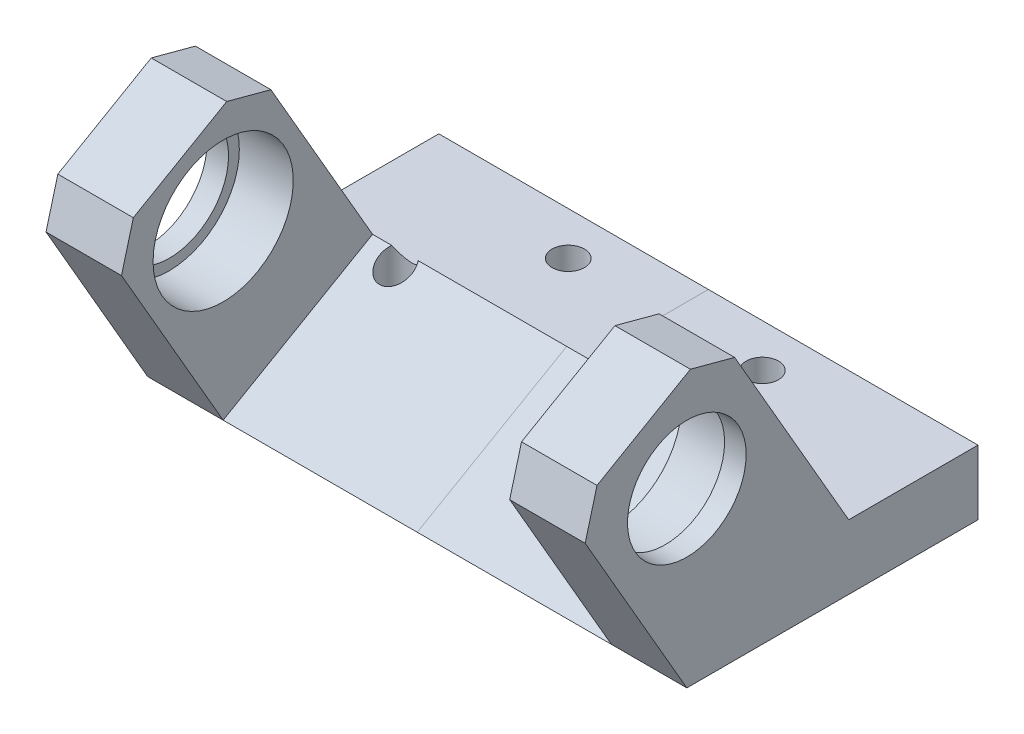
SolidWorks part; units mm, degrees
material "1060 合金"
ref_plane "前视基准面" through (0, 0, 0) normal (0, 0, 1) x (1, 0, 0)
ref_plane "上视基准面" through (0, 0, 0) normal (0, 1, 0) x (1, 0, 0)
ref_plane "右视基准面" through (0, 0, 0) normal (1, 0, 0) x (0, 0, -1)
sketch "草图1" plane through (0, 0, 0) normal (1, 0, 0) x (0, 0, -1)
  line L0 (0, 0) -> (-10.9282, 18.9282)
  line L1 (-10.9282, 18.9282) -> (2.9282, 26.9282)
  line L2 (2.9282, 26.9282) -> (15.0111, 6)
  line L3 (15.0111, 6) -> (27, 6)
  line L5 (27, 0) -> (0, 0)
  line L6 (27, 6) -> (27, 0)
  circle A0 centre (0, 16) radius 6.5
  dimension "D3" = 8
  dimension "D7" = 13
  dimension "D1" = 8
  dimension "D2" = 16
  dimension "D4" = 8
  dimension "D5" = 6
  dimension "D6" = 27
  dimension "D8" = 120
extrude "凸台-拉伸1" add sketch "草图1" along normal mid plane 50
chamfer "倒角1" distance 3 angle 45 2 edges at (0, 18.9282, 10.9282) (0, 26.9282, -2.9282)
sketch "草图2" plane through (0, 18.9282, 10.9282) normal (0, 0.866, 0.5) x (1, 0, 0)
  line L0 (0, 0) -> (0, 26.0074) construction
  line L1 (25, 0) -> (-25, 0) construction
  line L2 (25, 16) -> (-25, 16) construction
  line L3 (-18, 16) -> (18, 16)
  line L4 (-18, 16) -> (-18, 0)
  line L5 (-18, 0) -> (18, 0)
  line L6 (18, 16) -> (18, 0)
  line L7 (-18, 16) -> (18, 0) construction
  line L8 (-18, 0) -> (18, 16) construction
  line L9 (25, 13) -> (25, 3) construction
  point P4 (0, 8)
  dimension "D1" = 7
extrude "切除-拉伸1" cut sketch "草图2" against normal up to vertex (23.9132 mm away)
sketch "草图3" plane through (25, 0, 0) normal (1, 0, 0) x (0, 0, -1)
  circle A0 centre (0, 16) radius 6.5 construction
  circle A1 centre (0, 16) radius 6.5
  circle A2 centre (0, 16) radius 5.5
  dimension "D1" = 1
extrude "凸台-拉伸2" add sketch "草图3" against normal blind 2
mirror "镜向1" about plane through (0, 0, 0) normal (1, 0, 0) of "凸台-拉伸2"
hole_wizard "M3 螺纹孔1" positions "草图10" profile "草图11" tap size "M3" standard "GB" end condition through all
sketch "草图10" plane through (0, 0, 0) normal (0, -1, 0) x (-1, 0, 0)
  line L0 (0, 0) -> (0, 32.5589) construction
  line L1 (-25, 27) -> (25, 27) construction
  line L2 (-25, 27) -> (-25, 15.0111) construction
  point P8 (-15, 13)
  point P10 (-9, 23)
  point P12 (9, 23)
  point P14 (15, 13)
  dimension "D1" = 18
  dimension "D2" = 4
  dimension "D3" = 10
  dimension "D4" = 10
sketch "草图11" plane through (15, 0, -13) normal (1, 0, 0) x (0, 0, -1)
  line L0 (0, 0) -> (0, 25.4282)
  line L1 (0, 25.4282) -> (1.5, 25.4282)
  line L2 (1.5, 25.4282) -> (1.5, 0)
  line L5 (1.5, 0) -> (0, 0)
  line L11 (0, -6.35) -> (0, 107.95) construction
  dimension "螺纹线主直径" = 3
  dimension "通孔螺纹孔钻头深度" = 25.4282
split "分割1" trim tools "右视基准面" bodies to split 115 resulting bodies 116 117
move or copy body "实体-移动/复制1" [suppressed] bodies to move or copy 116 117
